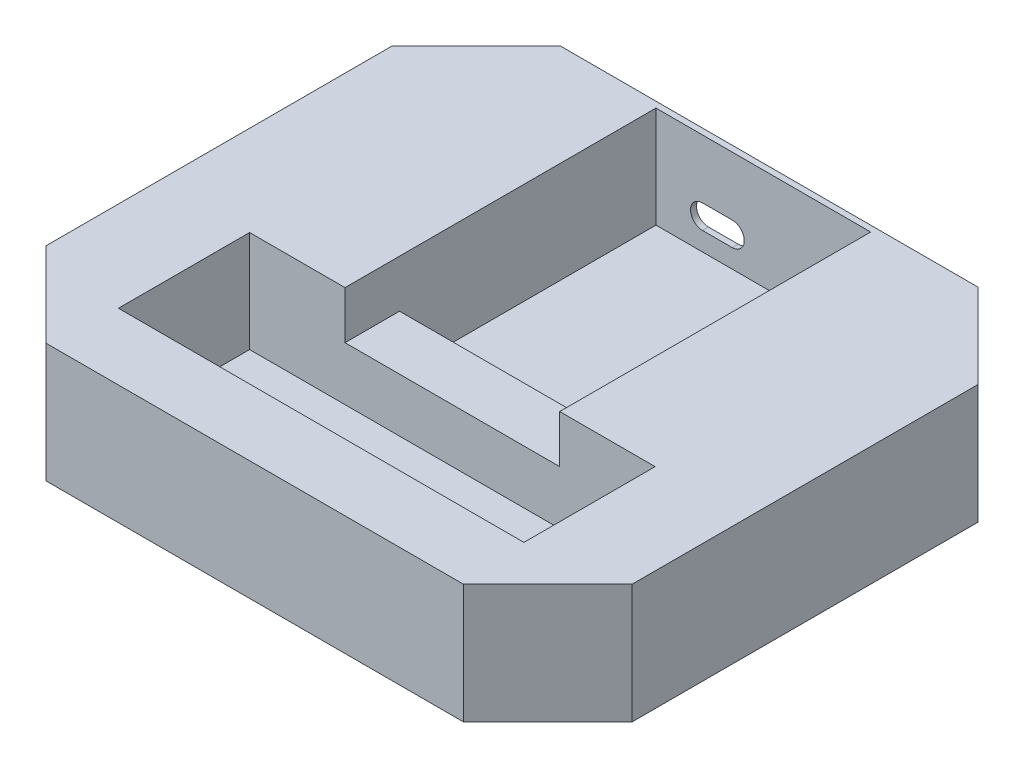
SolidWorks part; units mm, degrees
ref_plane "Front Plane" through (0, 0, 0) normal (0, 0, 1) x (1, 0, 0)
ref_plane "Top Plane" through (0, 0, 0) normal (0, 1, 0) x (1, 0, 0)
ref_plane "Right Plane" through (0, 0, 0) normal (1, 0, 0) x (0, 0, -1)
sketch "Sketch1" plane through (0, 0, 0) normal (0, 1, 0) x (1, 0, 0)
  line L0 (-35, 43.1421) -> (35, 43.1421)
  line L1 (35, 43.1421) -> (49.1421, 29)
  line L2 (49.1421, 29) -> (49.1421, -29)
  line L3 (49.1421, -29) -> (35, -43.1421)
  line L4 (35, -43.1421) -> (-35, -43.1421)
  line L5 (-35, -43.1421) -> (-49.1421, -29)
  line L6 (-49.1421, -29) -> (-49.1421, 29)
  line L7 (-49.1421, 29) -> (-35, 43.1421)
  line L8 (-49.1421, 0) -> (49.1421, 0) construction
  line L9 (0, 43.1421) -> (0, -43.1421) construction
  point P12 (0, 0)
  dimension "D1" = 70
  dimension "D2" = 20
  dimension "D3" = 58
  dimension "D4" = 135
extrude "Boss-Extrude1" add sketch "Sketch1" along normal blind 20
sketch "Sketch2" plane through (0, 20, 0) normal (0, 1, 0) x (1, 0, 0)
  line L0 (35, 43.1421) -> (-35, 43.1421) construction
  line L1 (-18, 42.1421) -> (18, 42.1421)
  line L2 (-18, 42.1421) -> (-18, -0.8579)
  line L3 (-18, -0.8579) -> (18, -0.8579)
  line L4 (18, 42.1421) -> (18, -0.8579)
  line L5 (-18, 42.1421) -> (18, -0.8579) construction
  line L6 (-18, -0.8579) -> (18, 42.1421) construction
  line L8 (-34, -10) -> (34, -10)
  line L9 (-34, -10) -> (-34, -32)
  line L10 (-34, -32) -> (34, -32)
  line L11 (34, -10) -> (34, -32)
  line L12 (-34, -10) -> (34, -32) construction
  line L13 (-34, -32) -> (34, -10) construction
  point P0 (0, 20.6421)
  point P10 (0, -21)
  dimension "D1" = 36
  dimension "D2" = 43
  dimension "D3" = 1
  dimension "D4" = 68
  dimension "D5" = 22
  dimension "D6" = 10
extrude "Cut-Extrude1" cut sketch "Sketch2" against normal blind 17
sketch "Sketch3" plane through (0, 20, 0) normal (0, 1, 0) x (1, 0, 0)
  line L0 (34, -10) -> (-34, -10) construction
  line L1 (-18, -10) -> (18, -10)
  line L2 (-18, -10) -> (-18, -0.8579)
  line L3 (-18, -0.8579) -> (18, -0.8579)
  line L4 (18, -10) -> (18, -0.8579)
  line L5 (-18, -10) -> (18, -0.8579) construction
  line L6 (-18, -0.8579) -> (18, -10) construction
  point P0 (0, -5.4289)
  dimension "D1" = 36
extrude "Cut-Extrude2" cut sketch "Sketch3" against normal blind 8
sketch "Sketch4" plane through (0, 0, -42.1421) normal (0, 0, 1) x (1, 0, 0)
  line L0 (-10.2, 8.13) -> (-5.2, 8.13) construction
  line L1 (-10.2, 10.13) -> (-5.2, 10.13)
  line L2 (-10.2, 6.13) -> (-5.2, 6.13)
  line L3 (18, 3) -> (-18, 3) construction
  line L4 (-18, 3) -> (-18, 20) construction
  arc A0 (-10.2, 10.13) -> (-10.2, 6.13) centre (-10.2, 8.13) ccw
  arc A1 (-5.2, 6.13) -> (-5.2, 10.13) centre (-5.2, 8.13) ccw
  point P2 (-7.7, 8.13)
  point P7 (-12.2, 8.13)
  point P8 (-3.2, 8.13)
  dimension "D2" = 9
  dimension "D4" = 5.8
  dimension "D1" = 4
  dimension "D3" = 3.13
extrude "Cut-Extrude3" cut sketch "Sketch4" against normal up to next
